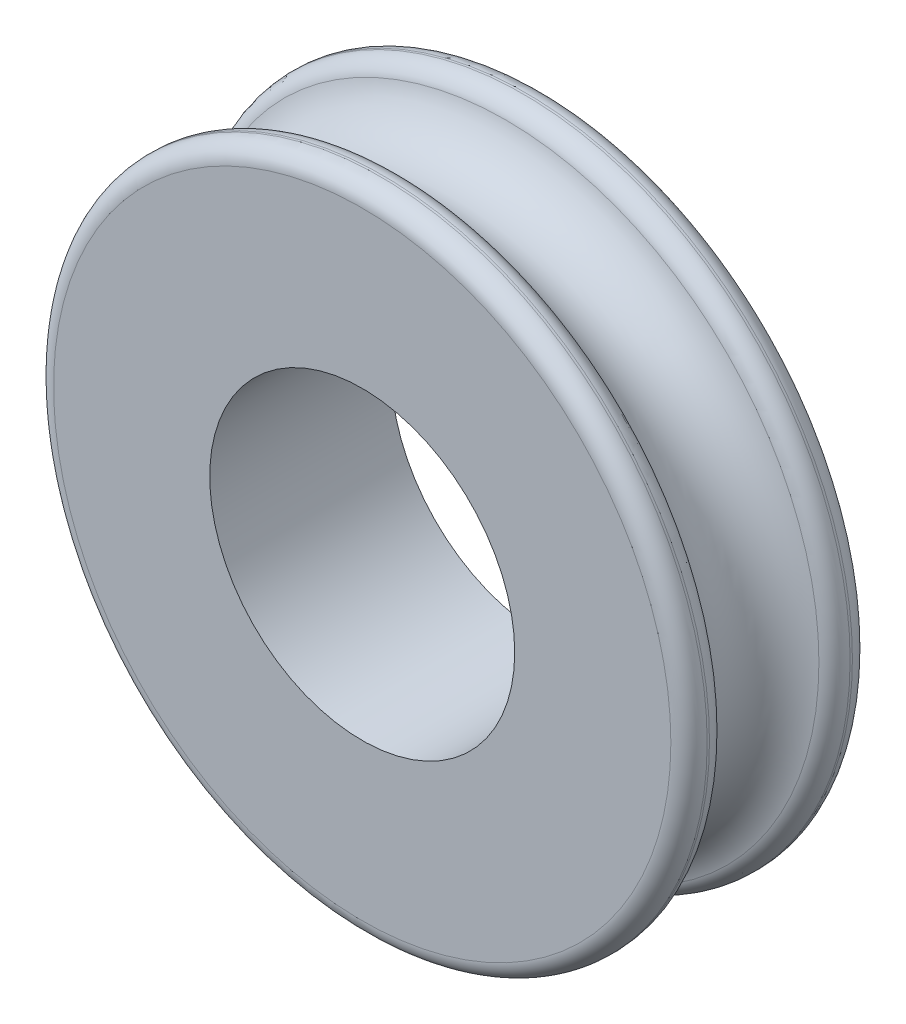
SolidWorks part; units mm, degrees
ref_plane "Front Plane" through (0, 0, 0) normal (0, 0, 1) x (1, 0, 0)
ref_plane "Top Plane" through (0, 0, 0) normal (0, 1, 0) x (1, 0, 0)
ref_plane "Right Plane" through (0, 0, 0) normal (1, 0, 0) x (0, 0, -1)
sketch "Эскиз1" plane through (0, 0, 0) normal (0, 0, 1) x (1, 0, 0)
  circle A0 centre (0, 0) radius 4.2
  circle A1 centre (0, 0) radius 9
  dimension "D1" = 8.4
  dimension "D2" = 18
extrude "Бобышка-Вытянуть1" add sketch "Эскиз1" along normal mid plane 5
sketch "Эскиз3" plane through (0, 0, 0) normal (0, 1, 0) x (1, 0, 0)
  line L0 (-13.6733, 0) -> (12.4977, 0) construction
  line L2 (9, -2.5) -> (9, 2.5) construction
  circle A0 centre (9, 0) radius 1.5
  point P5 (9, 0)
  dimension "D1" = 3
sketch "Эскиз4" plane through (0, 0, 0) normal (0, 0, 1) x (1, 0, 0)
  circle A0 centre (0, 0) radius 9 construction
  circle A1 centre (0, 0) radius 9
sweep "Вырез-По траектории1" cut profiles "Эскиз3" path "Эскиз4"
fillet "Скругление1" radius 0.5 2 edges at (9, 0, 2.5) (9, 0, -2.5)
fillet "Скругление2" radius 0.5 2 edges at (-9, 0, 1.5) (9, 0, -1.5)
